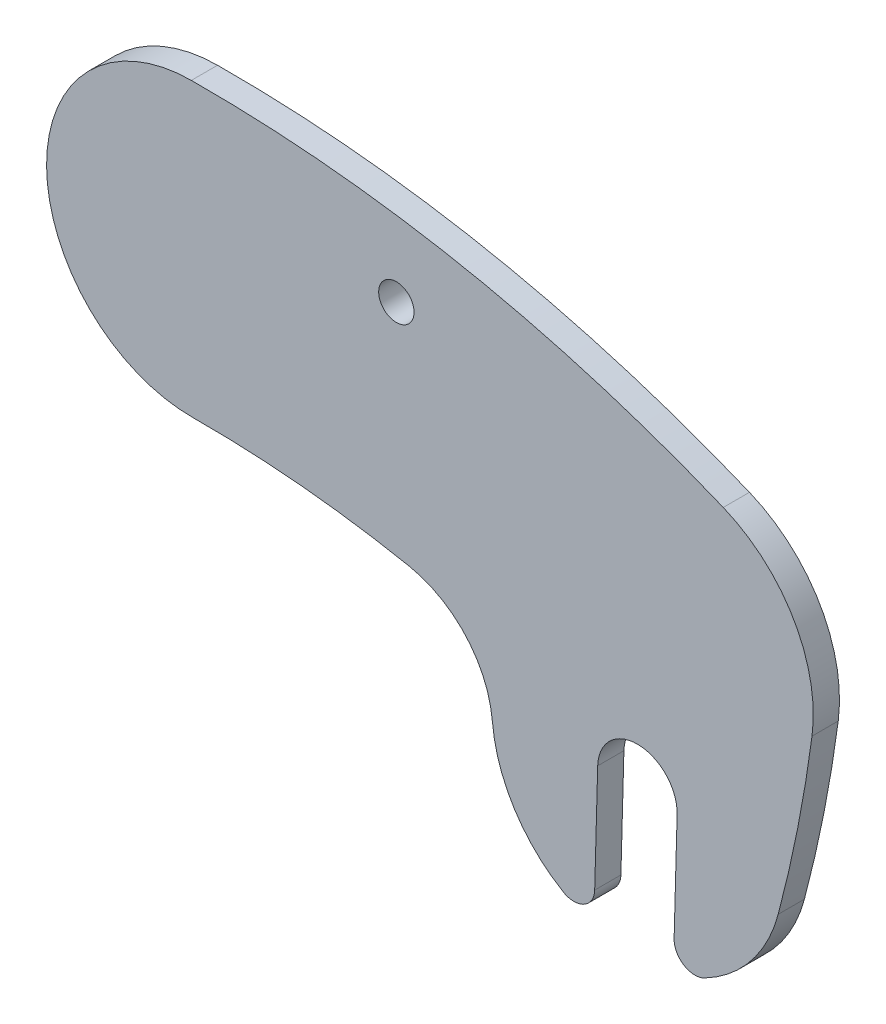
SolidWorks part; units mm, degrees
ref_plane "Front Plane" through (0, 0, 0) normal (0, 0, 1) x (1, 0, 0)
ref_plane "Top Plane" through (0, 0, 0) normal (0, 1, 0) x (1, 0, 0)
ref_plane "Right Plane" through (0, 0, 0) normal (1, 0, 0) x (0, 0, -1)
sketch "Sketch1" plane through (0, 0, 0) normal (0, 0, 1) x (1, 0, 0)
  line L84 (-6.7901, 16.4357) -> (6.7901, -16.4357) construction
  line L85 (121.0901, 16.4357) -> (107.5099, -16.4357) construction
  line L86 (0, 0) -> (114.3, 0) construction
  arc A81 (-6.7901, 16.4357) -> (121.0901, 16.4357) centre (57.15, -138.3341) cw
  arc A82 (6.7901, -16.4357) -> (107.5099, -16.4357) centre (57.15, -138.3341) cw
  arc A84 (-6.7901, 16.4357) -> (6.7901, -16.4357) centre (0, 0) ccw
  arc A85 (121.0901, 16.4357) -> (107.5099, -16.4357) centre (114.3, 0) cw
  dimension "D10" = 131.8914
  dimension "D11" = 35.5662
  dimension "D12" = 114.3
extrude "Boss-Extrude1" add sketch "Sketch1" along normal blind 3.2004
sketch "Sketch3" plane through (0, 0, 3.2004) normal (0, 0, 1) x (1, 0, 0)
  line L0 (114.3, 0) -> (110.6075, -18.6887) construction
  line L1 (131.9298, -2.3297) -> (96.6702, 2.3297) construction
  line L5 (121.0901, 16.4357) -> (107.5099, -16.4357) construction
  line L6 (0, 0) -> (114.3, 0) construction
  line L7 (93.4164, -14.1385) -> (127.7986, -23.2389) construction
  arc A0 (96.6702, 2.3297) -> (131.9298, -2.3297) centre (114.3, 0) cw
  arc A2 (93.4164, -14.1385) -> (127.7986, -23.2389) centre (110.6075, -18.6887) ccw
  arc A3 (96.6702, 2.3297) -> (93.4164, -14.1385) centre (-34.0845, 19.6087) cw
  arc A4 (131.9298, -2.3297) -> (127.7986, -23.2389) centre (-34.0845, 19.6087) cw
  dimension "D1" = 131.8914
  dimension "D2" = 19.05
  dimension "D3" = 78.823
extrude "Boss-Extrude2" add sketch "Sketch3" against normal up to surface (3.2004 mm away) up to face at (57.15, 2.2751, 0)
sketch "Sketch7" plane through (0, 0, 3.2004) normal (0, 0, 1) x (1, 0, 0)
  line L85 (115.457, -18.8224) -> (105.7579, -18.5551) construction
  line L86 (115.457, -18.8224) -> (114.6726, -47.288)
  line L87 (114.6726, -47.288) -> (104.9734, -47.0207)
  line L88 (105.7579, -18.5551) -> (104.9734, -47.0207)
  circle A0 centre (110.6075, -18.6887) radius 3.429 construction
  arc A1 (93.4164, -14.1385) -> (127.7986, -23.2389) centre (110.6075, -18.6887) ccw construction
  circle A82 centre (110.6075, -18.6887) radius 12.7 construction
  arc A83 (115.457, -18.8224) -> (105.7579, -18.5551) centre (110.6075, -18.6887) ccw
  point P5 (104.81, -16.6687)
  dimension "D1" = 6.858
  dimension "D9" = 25.4
  dimension "D10" = 9.7028
fillet "Fillet1" radius 12.7 1 edges at (94.0356, -11.7056, 1.6002)
extrude "Cut-Extrude3" cut sketch "Sketch7" against normal up to surface (3.2004 mm away) up to face at (77.6563, -5.4314, 0)
fillet "Fillet2" radius 2.54 2 edges at (105.2866, -35.6571, 1.6002) (114.9857, -35.9244, 1.6002)
sketch "Sketch9" plane through (0, 0, 0) normal (0, 0, -1) x (-1, 0, 0)
  circle A0 centre (-81.1715, 18.1918) radius 2.159
  dimension "D1" = 4.318
extrude "Cut-Extrude4" cut sketch "Sketch9" against normal up to surface (3.2004 mm away) up to face at (92.8075, -14.8113, 3.2004)
sketch "Sketch10" plane through (0, 0, 0) normal (0, 0, -1) x (-1, 0, 0)
  line L1 (-56.1348, 29.1204) -> (25.762, 49.5844)
  line L2 (-56.1348, 29.1204) -> (-56.3504, -6.4452) construction
  line L3 (-56.3504, -6.4452) -> (33.0274, -48.9539)
  line L4 (25.762, 49.5844) -> (33.0274, -48.9539)
  arc A0 (-56.1348, 29.1204) -> (-56.3504, -6.4452) centre (-56.2426, 11.3376) cw
  arc A1 (6.7901, 16.4357) -> (-121.0901, 16.4357) centre (-57.15, -138.3341) ccw construction
  arc A4 (-6.7901, -16.4357) -> (-82.7062, -8.9424) centre (-57.15, -138.3341) ccw construction
  point P11 (-54.4316, -6.1418)
  point P12 (-52.0009, 29.0443)
  point P13 (-56.2426, 11.3376)
  point P14 (25.762, 49.5844)
extrude "Cut-Extrude5" cut sketch "Sketch10" against normal up to surface (3.2004 mm away) up to face at (79.0125, 18.1918, 3.2004)
